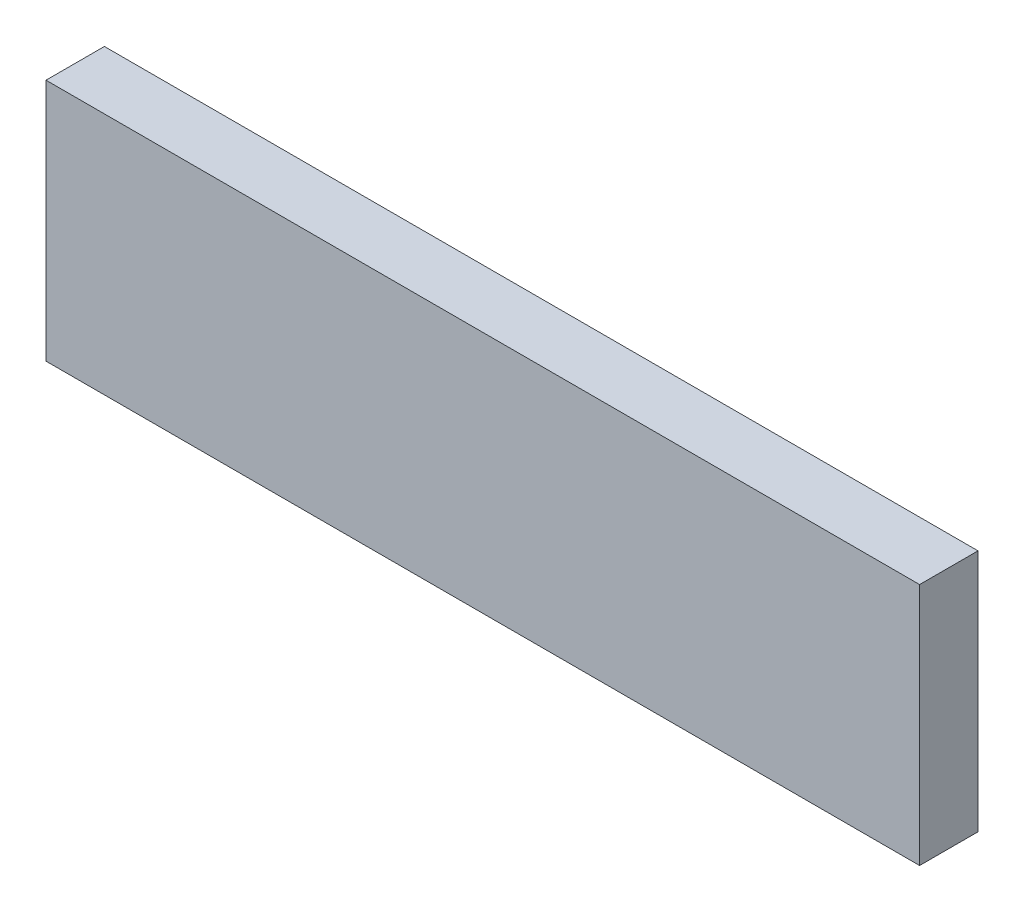
SolidWorks part; units mm, degrees
ref_plane "Plano frontal" through (0, 0, 0) normal (0, 0, 1) x (1, 0, 0)
ref_plane "Plano superior" through (0, 0, 0) normal (0, 1, 0) x (1, 0, 0)
ref_plane "Plano direito" through (0, 0, 0) normal (1, 0, 0) x (0, 0, -1)
sketch "Esboço1" plane through (0, 0, 0) normal (0, 0, 1) x (1, 0, 0)
  line L1 (-89.75, 25) -> (89.75, 25)
  line L2 (-89.75, 25) -> (-89.75, -25)
  line L3 (-89.75, -25) -> (89.75, -25)
  line L4 (89.75, 25) -> (89.75, -25)
  line L5 (-89.75, 25) -> (89.75, -25) construction
  line L6 (-89.75, -25) -> (89.75, 25) construction
  point P0 (0, 0)
extrude "Ressalto-extrusão1" add sketch "Esboço1" along normal mid plane 12
ref_plane "Plano1" through (0, -25, 0) normal (0, -1, 0) x (-1, 0, 0)
sketch "Esboço2" plane through (0, -25, 0) normal (0, -1, 0) x (-1, 0, 0)
  circle A0 centre (71.25, 0) radius 1.5
  circle A1 centre (-83.75, 0) radius 1.5
extrude "Corte-extrusão1" cut sketch "Esboço2" against normal mid plane 30
